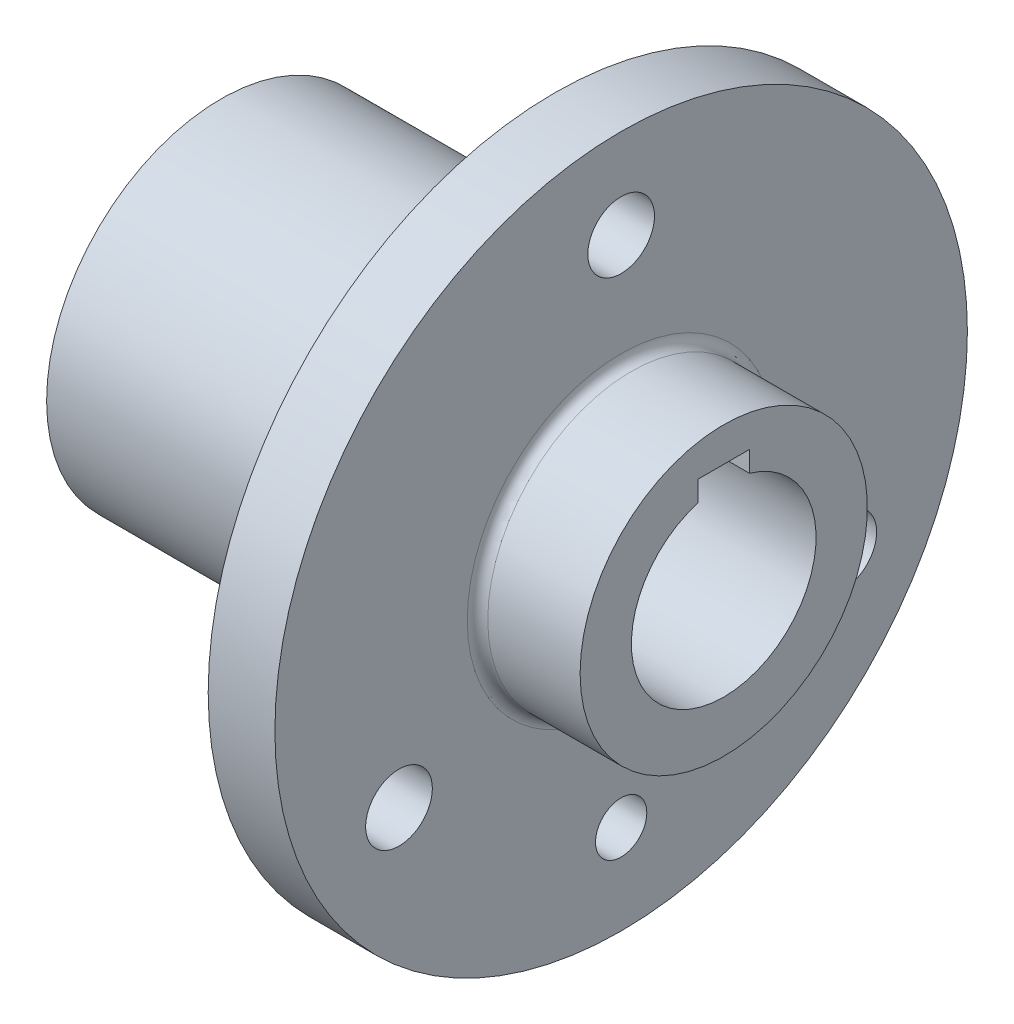
SolidWorks part; units mm, degrees
ref_plane "Front Plane" through (0, 0, 0) normal (0, 0, 1) x (1, 0, 0)
ref_plane "Top Plane" through (0, 0, 0) normal (0, 1, 0) x (1, 0, 0)
ref_plane "Right Plane" through (0, 0, 0) normal (1, 0, 0) x (0, 0, -1)
sketch "Sketch1" plane through (0, 0, 0) normal (0, 0, 1) x (1, 0, 0)
  line L0 (-48.7466, -10) -> (21.5294, -10) construction
  line L1 (-48.7466, 0) -> (-48.7466, 5)
  line L2 (-48.7466, 5) -> (-43.7466, 5)
  line L3 (-43.7466, 5) -> (-43.7466, 24)
  line L4 (-43.7466, 24) -> (21.2534, 24)
  line L5 (21.2534, 24) -> (21.2534, 57.5)
  line L6 (21.2534, 57.5) -> (34.2534, 57.5)
  line L7 (34.2534, 57.5) -> (34.2534, 18)
  line L8 (34.2534, 18) -> (54.2534, 18)
  line L9 (54.2534, 8) -> (54.2534, 18)
  line L10 (-48.7466, 0) -> (-36.7466, 0)
  line L11 (-36.7466, 0) -> (-33.7466, 3)
  line L12 (-33.7466, 3) -> (-33.7466, 14)
  line L13 (-33.7466, 14) -> (2.2534, 14)
  line L14 (2.2534, 14) -> (2.2534, 8)
  line L15 (2.2534, 8) -> (54.2534, 8)
  dimension "D1" = 10
  dimension "D2" = 15
  dimension "D3" = 34
  dimension "D4" = 24
  dimension "D5" = 12
  dimension "D6" = 36
  dimension "D7" = 52
  dimension "D8" = 98
  dimension "D9" = 20
  dimension "D10" = 13
  dimension "D11" = 67.5
  dimension "D12" = 28
  dimension "D13" = 5
  dimension "D14" = 225
  dimension "D15" = 18
revolve "Revolve1" add sketch "Sketch1" angle 360 about L0
fillet "Fillet1" radius 2 3 edges at (34.2534, -10, 28) (21.2534, -10, 34) (-43.7466, -10, 15)
fillet "Fillet2" radius 2 2 edges at (2.2534, -10, 18) (-33.7466, -10, 24)
sketch "Sketch2" plane through (54.2534, 0, 0) normal (1, 0, 0) x (0, 0, -1)
  line L0 (0, -28) -> (12.1375, -28.5458) construction
  line L1 (-5, 4.7) -> (5, 4.7)
  line L2 (-5, 4.7) -> (-5, 11.3)
  line L3 (-5, 11.3) -> (5, 11.3)
  line L4 (5, 4.7) -> (5, 11.3)
  line L5 (-5, 4.7) -> (5, 11.3) construction
  line L6 (-5, 11.3) -> (5, 4.7) construction
  line L7 (0, 8) -> (0, -10) construction
  line L8 (0, -10) -> (0, -28) construction
  circle A0 centre (0, -10) radius 18 construction
  point P0 (0, 8)
  dimension "D1" = 10
  dimension "D2" = 39.3
extrude "Cut-Extrude1" cut sketch "Sketch2" against normal blind 52
sketch "Sketch3" plane through (34.2534, 0, 0) normal (1, 0, 0) x (0, 0, -1)
  line L0 (0, -10) -> (0, 20) construction
  line L1 (0, 20) -> (0, -10) construction
  line L2 (0, -10) -> (0, -43.4367) construction
  line L3 (0, 20) -> (0, 57.5) construction
  line L4 (0, -43.4367) -> (0, -77.5) construction
  circle A0 centre (0, -10) radius 30 construction
  circle A1 centre (0, -10) radius 67.5 construction
  circle A2 centre (0, 40) radius 6.5
  circle A3 centre (43.3013, -35) radius 6.5
  circle A4 centre (-43.3013, -35) radius 6.5
  circle A5 centre (0, -60) radius 5
  point P22 (0, -10)
  dimension "D1" = 13
  dimension "D4" = 10
  dimension "D2" = 50
  dimension "D5" = 50
  dimension "D3" = 3
extrude "Cut-Extrude2" cut sketch "Sketch3" against normal blind 52
